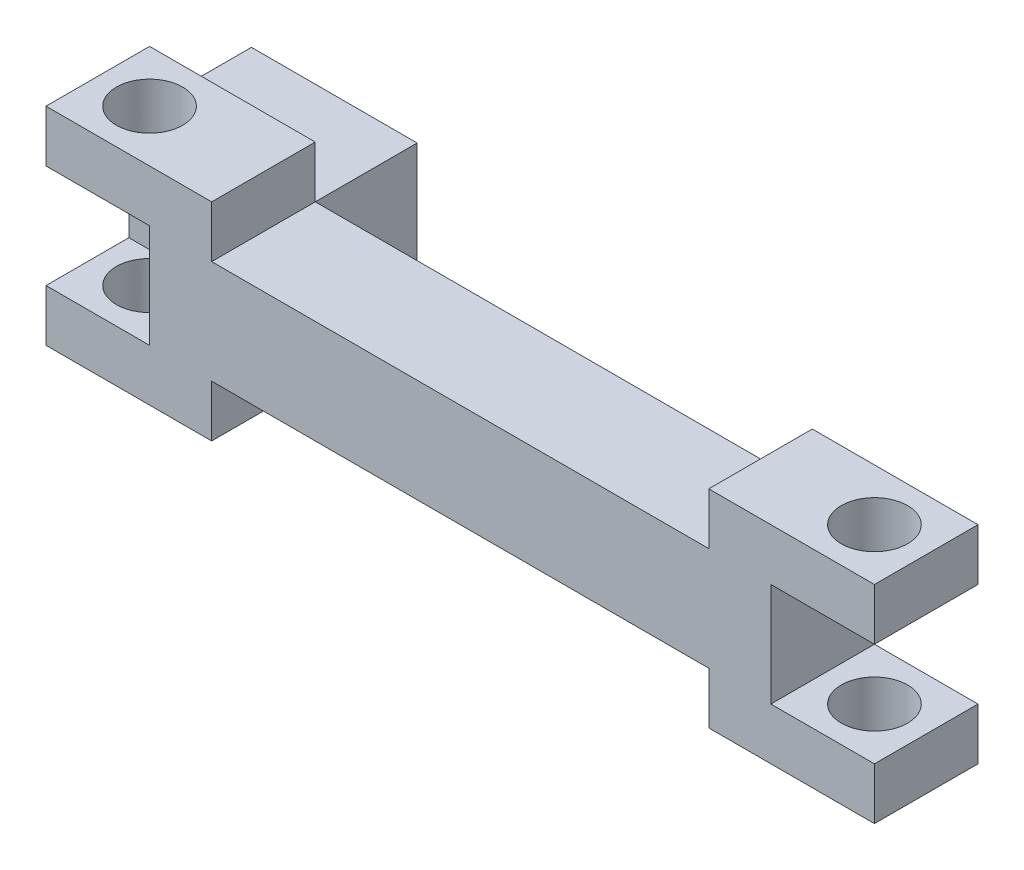
SolidWorks part; units mm, degrees
ref_plane "Front Plane" through (0, 0, 0) normal (0, 0, 1) x (1, 0, 0)
ref_plane "Top Plane" through (0, 0, 0) normal (0, 1, 0) x (1, 0, 0)
ref_plane "Right Plane" through (0, 0, 0) normal (1, 0, 0) x (0, 0, -1)
sketch "Sketch1" plane through (0, 0, 0) normal (0, 0, 1) x (1, 0, 0)
  line L0 (-60.8, 45) -> (-60.8, 57.5)
  line L1 (-60.8, 45) -> (59.2, 45)
  line L2 (-100.8, 45) -> (-100.8, 20)
  line L3 (-60.8, 20) -> (59.2, 20)
  line L5 (-100.8, 7.5) -> (-60.8, 7.5)
  line L6 (-100.8, 7.5) -> (-100.8, 57.5)
  line L7 (-100.8, 57.5) -> (-60.8, 57.5)
  line L8 (-60.8, 7.5) -> (-60.8, 20)
  line L9 (74.2, 20) -> (74.2, 45)
  line L10 (59.2, 57.5) -> (99.2, 57.5)
  line L11 (59.2, 57.5) -> (59.2, 45)
  line L12 (59.2, 7.5) -> (99.2, 7.5)
  line L13 (99.2, 57.5) -> (99.2, 45)
  line L14 (59.2, 20) -> (59.2, 7.5)
  line L15 (74.2, 45) -> (99.2, 45)
  line L16 (74.2, 20) -> (99.2, 20)
  line L17 (99.2, 20) -> (99.2, 7.5)
  dimension "D1" = 200
  dimension "D2" = 25
  dimension "D3" = 40
  dimension "D4" = 50
  dimension "D5" = 50
  dimension "D6" = 40
  dimension "D7" = 200
extrude "Boss-Extrude1" add sketch "Sketch1" along normal blind 25 contours L17 L16 L9 L15 L13 L10 L11 L1 L0 L7 L6 L2 L5 L8 L3 L14 L12
sketch "Sketch2" plane through (0, 57.5, 0) normal (0, 1, 0) x (1, 0, 0)
  line L0 (-100.8, 0) -> (-60.8, 0) construction
  line L2 (-100.8, -25) -> (-100.8, 0) construction
  circle A0 centre (-88.3, -12.5) radius 8
  dimension "D1" = 16
  dimension "D2" = 12.5
  dimension "D3" = 12.5
extrude "Cut-Extrude1" cut sketch "Sketch2" against normal blind 70.5
sketch "Sketch3" plane through (0, 57.5, 0) normal (0, 1, 0) x (1, 0, 0)
  line L0 (99.2, -25) -> (99.2, 0) construction
  line L1 (59.2, 0) -> (99.2, 0) construction
  circle A0 centre (86.7, -12.5) radius 8
  dimension "D1" = 16
  dimension "D2" = 12.5
  dimension "D3" = 12.5
extrude "Cut-Extrude2" cut sketch "Sketch3" against normal blind 88
sketch "Sketch4" plane through (0, 0, 0) normal (0, 0, -1) x (-1, 0, 0)
  line L0 (100.8, 7.5) -> (100.8, 57.5) construction
  line L1 (60.8, 45) -> (100.8, 45)
  line L2 (60.8, 45) -> (60.8, 20)
  line L3 (60.8, 20) -> (100.8, 20)
  line L4 (100.8, 45) -> (100.8, 20)
  line L5 (60.8, 20) -> (-59.2, 20) construction
  dimension "D1" = 0
extrude "Boss-Extrude2" add sketch "Sketch4" along normal blind 24.6
sketch "Sketch5" plane through (0, 0, -24.6) normal (0, 0, -1) x (-1, 0, 0)
  line L0 (100.8, 45) -> (60.8, 45) construction
  line L1 (100.8, 20) -> (100.8, 45) construction
  circle A0 centre (85.8, 32.5) radius 7.5
  dimension "D1" = 15
  dimension "D2" = 12.5
  dimension "D3" = 15
extrude "Cut-Extrude4" cut sketch "Sketch5" against normal blind 12.5
sketch "Sketch7" plane through (0, 0, 25) normal (0, 0, 1) x (1, 0, 0)
  line L1 (-75.8, 20) -> (-100.8, 20)
  line L2 (-75.8, 20) -> (-75.8, 45)
  line L3 (-75.8, 45) -> (-100.8, 45)
  line L4 (-100.8, 20) -> (-100.8, 45)
  dimension "D1" = 25
  dimension "D2" = 25
extrude "Cut-Extrude6" cut sketch "Sketch7" against normal blind 20
